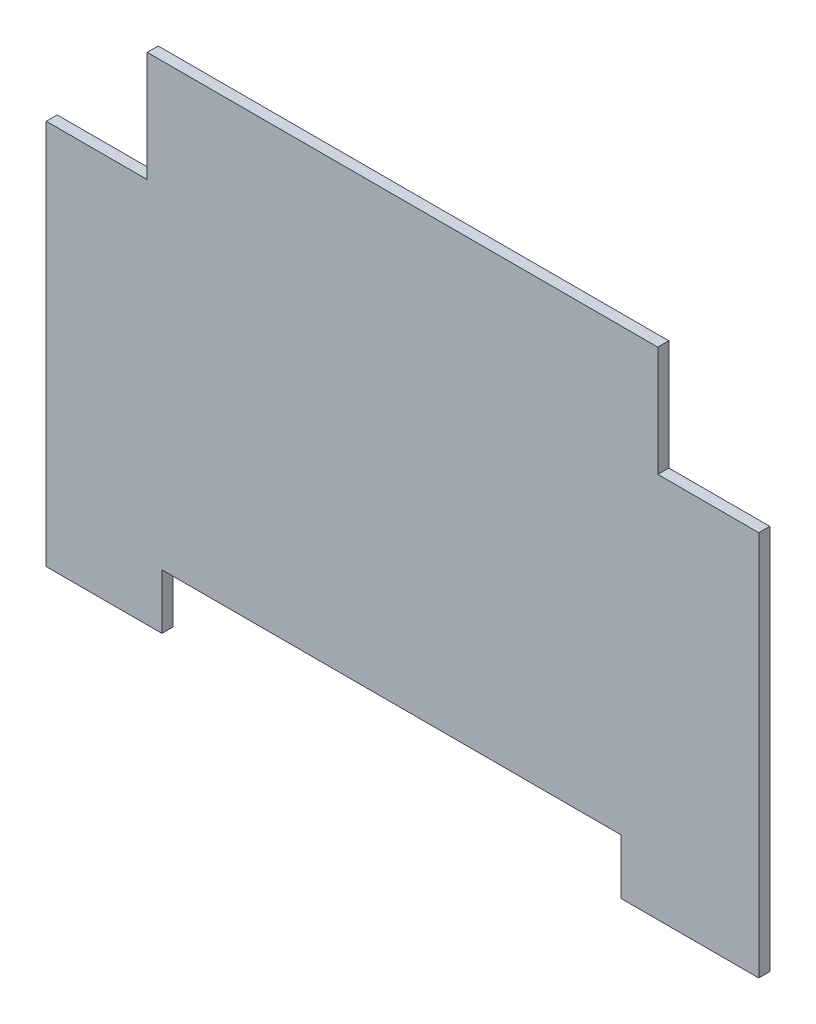
SolidWorks part; units mm, degrees
material "Pine"
ref_plane "Front Plane" through (0, 0, 0) normal (0, 0, 1) x (1, 0, 0)
ref_plane "Top Plane" through (0, 0, 0) normal (0, 1, 0) x (1, 0, 0)
ref_plane "Right Plane" through (0, 0, 0) normal (1, 0, 0) x (0, 0, -1)
sketch "Sketch1" plane through (0, 0, 0) normal (0, 0, 1) x (1, 0, 0)
  line L1 (-110.8686, 260.6668) -> (277.1314, 260.6668)
  line L2 (-110.8686, 260.6668) -> (-110.8686, -9.3332)
  line L3 (-110.8686, -9.3332) -> (277.1314, -9.3332)
  line L4 (277.1314, 260.6668) -> (277.1314, -9.3332)
  dimension "D1" = 388
  dimension "D2" = 270
extrude "Boss-Extrude1" add sketch "Sketch1" along normal blind 6
sketch "Sketch2" plane through (0, 0, 0) normal (0, 0, -1) x (-1, 0, 0)
  line L1 (-277.1314, 200.6668) -> (-222.1314, 200.6668)
  line L2 (-277.1314, 200.6668) -> (-277.1314, 260.6668)
  line L3 (-277.1314, 260.6668) -> (-222.1314, 260.6668)
  line L4 (-222.1314, 200.6668) -> (-222.1314, 260.6668)
  line L5 (110.8686, 200.6668) -> (55.8686, 200.6668)
  line L6 (110.8686, 200.6668) -> (110.8686, 260.6668)
  line L7 (110.8686, 260.6668) -> (55.8686, 260.6668)
  line L8 (55.8686, 200.6668) -> (55.8686, 260.6668)
  line L9 (110.8686, 260.6668) -> (110.8686, -9.3332) construction
  line L10 (-277.1314, 260.6668) -> (110.8686, 260.6668) construction
  line L11 (-277.1314, -9.3332) -> (-277.1314, 260.6668) construction
  dimension "D1" = 55
  dimension "D2" = 55
  dimension "D3" = 60
  dimension "D4" = 60
  dimension "D5" = 0
  dimension "D6" = 0
  dimension "D7" = 0
  dimension "D8" = 0
extrude "Cut-Extrude1" cut sketch "Sketch2" against normal blind 40
sketch "Sketch3" plane through (0, 0, 0) normal (0, 0, -1) x (-1, 0, 0)
  line L0 (110.8686, -9.3332) -> (-277.1314, -9.3332) construction
  line L1 (47.8686, 20.6668) -> (-202.1314, 20.6668)
  line L2 (47.8686, 20.6668) -> (47.8686, -9.3332)
  line L3 (47.8686, -9.3332) -> (-202.1314, -9.3332)
  line L4 (-202.1314, 20.6668) -> (-202.1314, -9.3332)
  line L5 (-277.1314, -9.3332) -> (-277.1314, 200.6668) construction
  dimension "D1" = 0
  dimension "D2" = 250
  dimension "D3" = 30
  dimension "D4" = 75
extrude "Cut-Extrude2" cut sketch "Sketch3" against normal blind 10
